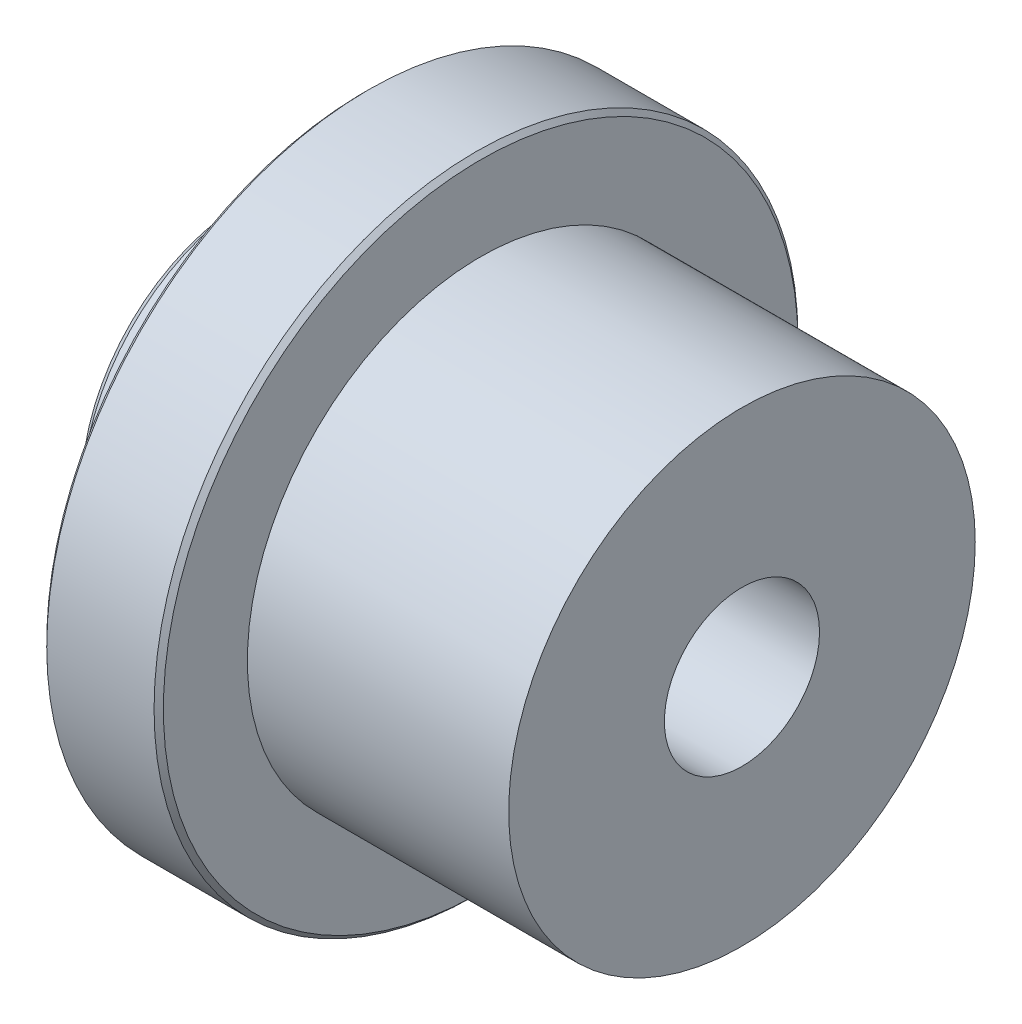
SolidWorks part; units mm, degrees
ref_plane "Front Plane" through (0, 0, 0) normal (0, 0, 1) x (1, 0, 0)
ref_plane "Top Plane" through (0, 0, 0) normal (0, 1, 0) x (1, 0, 0)
ref_plane "Right Plane" through (0, 0, 0) normal (1, 0, 0) x (0, 0, -1)
sketch "Sketch1" plane through (0, 0, 0) normal (1, 0, 0) x (0, 0, -1)
  circle A0 centre (0, 0) radius 17.526
  circle A1 centre (0, 0) radius 3.9688
extrude "Boss-Extrude1" add sketch "Sketch1" along normal blind 6.35
sketch "Sketch2" plane through (0, 0, 0) normal (0, 0, 1) x (1, 0, 0)
  circle A0 centre (3.175, 0) radius 1.9685
extrude "Cut-Extrude1" [suppressed] cut sketch "Sketch2" along normal blind 26.162
chamfer "Chamfer1" [suppressed] distance 0.254 angle 45
chamfer "Chamfer2" distance 0.254 angle 45 4 edges at (6.35, 0, -3.9688) (6.35, 0, -17.526) (0, 0, -3.9688) (0, 0, -17.526)
sketch "Sketch3" plane through (0, 0, 0) normal (-1, 0, 0) x (0, 0, 1)
  circle A0 centre (0, 0) radius 9.525
  circle A1 centre (0, 0) radius 3.9688
extrude "Boss-Extrude2" add sketch "Sketch3" along normal blind 6.35
chamfer "Chamfer3" distance 0.508 angle 45 2 edges at (0, 0, -9.525) (-6.35, 0, 9.525)
sketch "Sketch8" plane through (6.35, 0, 0) normal (1, 0, 0) x (0, 0, -1)
  circle A0 centre (0, 0) radius 4.2227
  circle A1 centre (0, 0) radius 12.7
extrude "Boss-Extrude3" add sketch "Sketch8" along normal blind 14.224
sketch "Sketch6" plane through (0, 0, 0) normal (0, 0, 1) x (1, 0, 0)
  circle A0 centre (-3.175, 0) radius 1.9685
  circle A1 centre (13.462, 0) radius 1.9685
extrude "Cut-Extrude2" cut sketch "Sketch6" against normal blind 16.764
